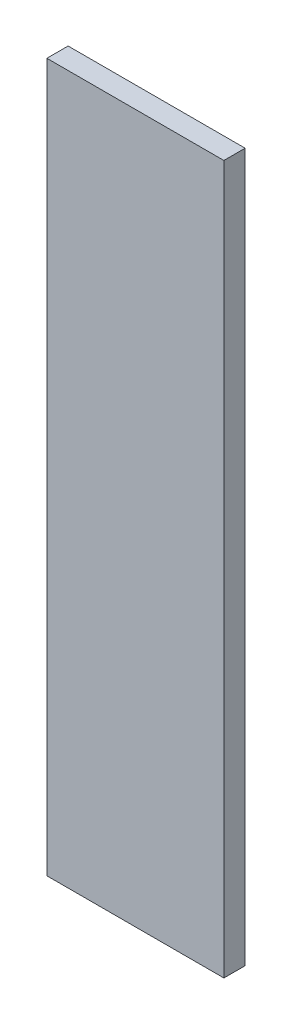
SolidWorks part; units mm, degrees
ref_plane "Front Plane" through (0, 0, 0) normal (0, 0, 1) x (1, 0, 0)
ref_plane "Top Plane" through (0, 0, 0) normal (0, 1, 0) x (1, 0, 0)
ref_plane "Right Plane" through (0, 0, 0) normal (1, 0, 0) x (0, 0, -1)
sketch "WingSketch" plane through (0, 0, 0) normal (0, 1, 0) x (1, 0, 0)
  line L1 (-500, -60) -> (500, -60)
  line L2 (-500, -60) -> (-500, 60)
  line L3 (-500, 60) -> (500, 60)
  line L4 (500, -60) -> (500, 60)
  point P0 (0, 0)
  dimension "D1" = 120
  dimension "D2" = 60
  dimension "D3" = 1000
  dimension "D4" = 500
extrude "RectangualrWing" add sketch "WingSketch" along normal mid plane 4000
